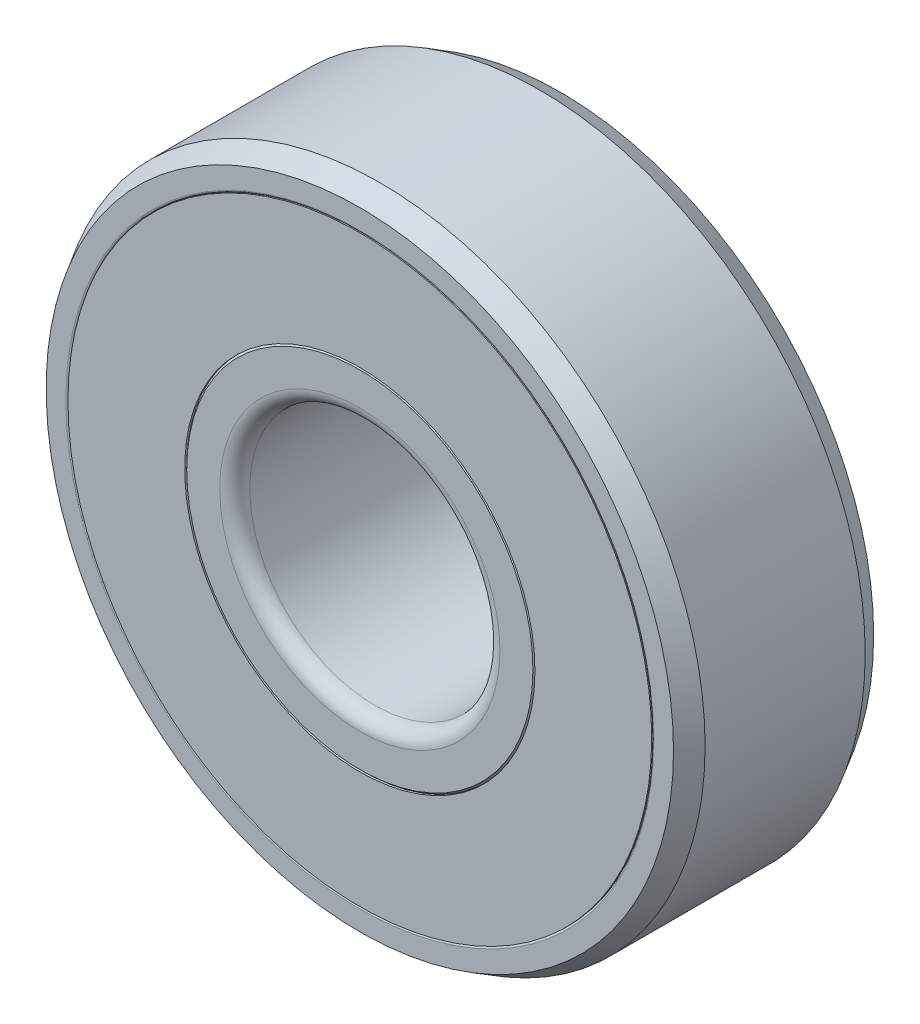
SolidWorks part; units mm, degrees
ref_plane "Front Plane" through (0, 0, 0) normal (0, 0, 1) x (1, 0, 0)
ref_plane "Top Plane" through (0, 0, 0) normal (0, 1, 0) x (1, 0, 0)
ref_plane "Right Plane" through (0, 0, 0) normal (1, 0, 0) x (0, 0, -1)
sketch "Sketch1" plane through (0, 0, 0) normal (0, 0, 1) x (1, 0, 0)
  line L0 (0, 4.5) -> (0, 6.5) construction
  line L1 (0, 2.5) -> (0, 4.5) construction
  line L2 (0, 6.5) -> (0, 5.8333) construction
  line L3 (0, 5.8333) -> (0, 5.1667) construction
  line L4 (0, 5.1667) -> (0, 4.5) construction
  circle A0 centre (0, 0) radius 2.5
  circle A1 centre (0, 0) radius 6.5
  circle A2 centre (0, 0) radius 5.8333 construction
  circle A4 centre (0, 0) radius 3.5 construction
  point P6 (0, 3.5)
  dimension "OD" = 13
  dimension "ID" = 5
sketch "Sketch2" plane through (0, 0, 0) normal (1, 0, 0) x (0, 0, -1)
  line L0 (-2, 6.5) -> (2, 6.5) construction
  line L1 (2, 6.5) -> (2, -6.5) construction
  line L2 (2, 0) -> (-2, 0) construction
  line L3 (-2, 2.5) -> (-2, -2.5) construction
  point P2 (0, 6.5)
  dimension "Width" = 4
  dimension "For Shaft Diameter" = 5
  dimension "For Housing ID" = 13
sketch "Sketch3" plane through (0, 0, 0) normal (1, 0, 0) x (0, 0, -1)
  line L0 (-1.6, -6.5) -> (1.6, -6.5)
  line L3 (-2, -5.8733) -> (-2, -6.2691)
  line L4 (0, -3.5) -> (0, -5.8333) construction
  line L5 (-1.6, -6.5) -> (-2, -6.2691)
  line L6 (-1.7, -2.5) -> (1.7, -2.5)
  line L7 (-1.1111, -5.8333) -> (-1.1111, -6.0556) construction
  line L8 (-1.96, -3.5) -> (-1.1111, -3.5)
  line L9 (-2, -3.5) -> (0, -3.5) construction
  line L11 (-2, -5.8333) -> (-2, -3.5) construction
  line L12 (-2, -3.46) -> (-2, -2.8)
  line L14 (-2, 0) -> (2, 0) construction
  line L15 (-1.96, -5.8333) -> (-1.1111, -5.8333)
  line L17 (0, 0) -> (0, -6.5) construction
  line L18 (-1.1111, -6.0556) -> (-1.1111, -6.2778) construction
  line L19 (1.6, -6.5) -> (2, -6.2691)
  line L20 (0, -5.8333) -> (-2, -5.8333) construction
  line L21 (-2, 2.5) -> (-2, -2.5) construction
  line L22 (-1.1111, -6.2778) -> (-1.1111, -6.5) construction
  line L30 (-2, -3.46) -> (-1.96, -3.5)
  line L31 (1.96, -3.5) -> (1.1111, -3.5)
  line L32 (2, -3.46) -> (1.96, -3.5)
  line L33 (2, -3.46) -> (2, -2.8)
  line L34 (1.96, -5.8333) -> (1.1111, -5.8333)
  line L35 (2, -5.8733) -> (2, -6.2691)
  line L36 (0, 6.5) -> (0, -6.5) construction
  arc A0 (0, -3.0556) -> (0, -6.2778) centre (0, -4.6667) ccw construction
  arc A1 (-1.1111, -3.5) -> (1.1111, -3.5) centre (0, -4.6667) cw
  arc A2 (-1.1111, -5.8333) -> (1.1111, -5.8333) centre (0, -4.6667) ccw
  arc A4 (-1.96, -5.8333) -> (-2, -5.8733) centre (-1.96, -5.8733) ccw
  arc A5 (-1.7, -2.5) -> (-2, -2.8) centre (-1.7, -2.8) ccw
  arc A6 (1.7, -2.5) -> (2, -2.8) centre (1.7, -2.8) cw
  arc A7 (1.96, -5.8333) -> (2, -5.8733) centre (1.96, -5.8733) cw
  point P28 (0, -4.6667)
  point P46 (-2, -2.5)
  point P54 (0, -2.5)
  dimension "D4" = 0.04
  dimension "D7" = 0.3
  dimension "D5" = 45
  dimension "D6" = 0.04
  dimension "D3" = 0.4
  dimension "D2" = 60
revolve "Revolve1" add sketch "Sketch3" angle 360 about L14
sketch "Sketch4" plane through (0, 0, 0) normal (1, 0, 0) x (0, 0, -1)
  line L0 (-1.96, -5.8333) -> (-1.1111, -5.8333) construction
  line L1 (-2, -3.5) -> (-1.7083, -3.5)
  line L2 (-2, -3.5) -> (-2, -5.8333)
  line L3 (-2, -5.8333) -> (-1.7083, -5.8333)
  line L4 (-1.7083, -3.5) -> (-1.7083, -5.8333)
  line L5 (-2, -3.46) -> (-2, -2.8) construction
  line L6 (-2, -4.6667) -> (-1.9028, -4.6667) construction
  line L7 (-1.9028, -4.6667) -> (-1.8056, -4.6667) construction
  line L8 (-1.8056, -4.6667) -> (-1.7083, -4.6667) construction
  line L9 (-1.7083, -4.6667) -> (-1.6111, -4.6667) construction
  line L10 (-2, -5.8333) -> (-2, -3.5) construction
  line L11 (-1.96, -3.5) -> (-1.1111, -3.5) construction
  arc A1 (0, -3.0556) -> (0, -6.2778) centre (0, -4.6667) ccw construction
revolve "Revolve2" add sketch "Sketch4" angle 360 about L14
sketch "Sketch5" plane through (0, 0, 0) normal (1, 0, 0) x (0, 0, -1)
  line L2 (0, -3.0556) -> (0, -6.2778)
  arc A2 (0, -6.2778) -> (0, -3.0556) centre (0, -4.6667) cw
revolve "Revolve3" add sketch "Sketch5" angle 360 about L17
pattern_circular "CirPattern1" count 7 over 360 about axis through (0, 0, 0) along (0, 0, 1) of bodies 138
equation "\"D4@Sketch3\"=\"Width@Sketch2\"*.01"
equation "\"D6@Sketch3\"=\"Width@Sketch2\"*.01"
equation "\"D7@Sketch3\"=\"Width@Sketch2\"*.075"
equation "\"D3@Sketch3\"=\"Width@Sketch2\"*.1"
